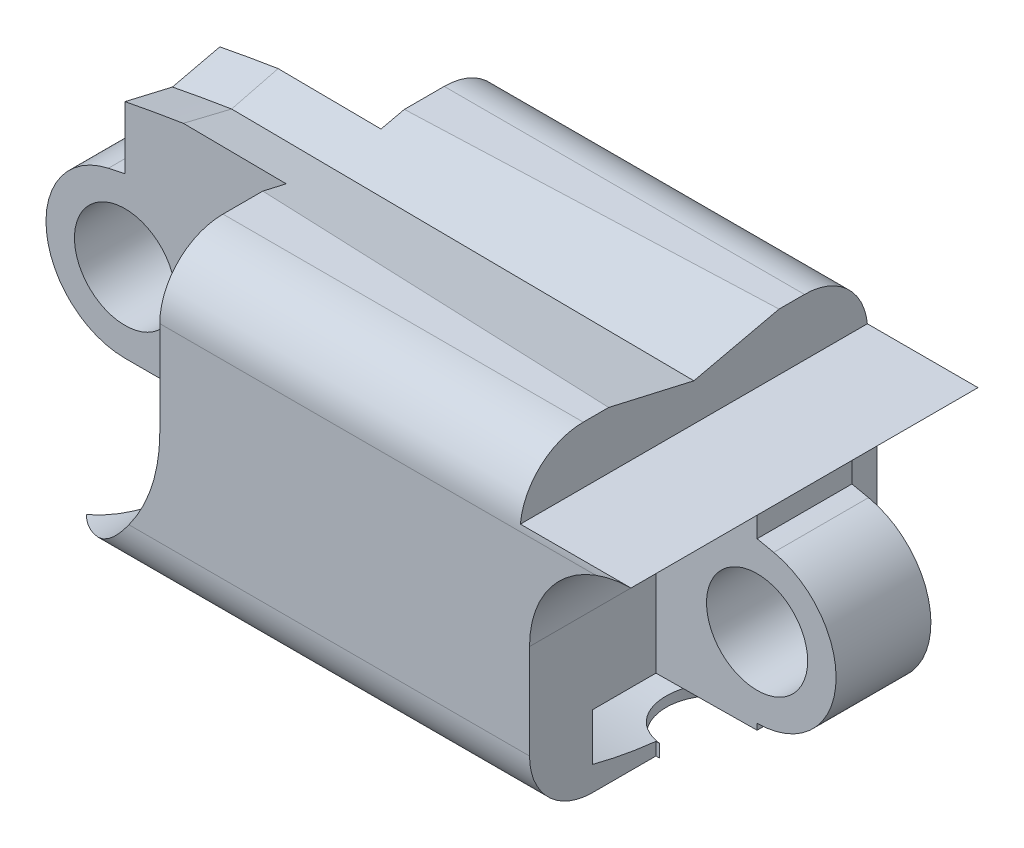
SolidWorks part; units mm, degrees
ref_plane "Front Plane" through (0, 0, 0) normal (0, 0, 1) x (1, 0, 0)
ref_plane "Top Plane" through (0, 0, 0) normal (0, 1, 0) x (1, 0, 0)
ref_plane "Right Plane" through (0, 0, 0) normal (1, 0, 0) x (0, 0, -1)
sketch "Sketch1" plane through (0, 0, 0) normal (0, 0, 1) x (1, 0, 0)
  line L0 (0, 0) -> (20, 0) construction
  line L1 (0, -2.5) -> (20, -2.5)
  circle A0 centre (0, 0) radius 1.6
  circle A1 centre (20, 0) radius 1.6
  arc A2 (-0.5263, 2.444) -> (0, -2.5) centre (0, 0) ccw
  arc A3 (20, -2.5) -> (20.5263, 2.444) centre (20, 0) ccw
  arc A4 (20.5263, 2.444) -> (-0.5263, 2.444) centre (10, -46.4354) ccw
  dimension "D2" = 3.2
  dimension "D3" = 3.2
  dimension "D4" = 5
  dimension "D5" = 5
  dimension "D6" = 50
  dimension "D1" = 20
extrude "Boss-Extrude1" add sketch "Sketch1" along normal mid plane 3
sketch "Sketch2" plane through (0, 0, 0) normal (0, 1, 0) x (1, 0, 0)
  line L0 (0, 0) -> (20, 0) construction
  line L1 (21.6, 1.5) -> (18.4, 1.5) construction
  line L2 (21.6, 1.5) -> (18.4, 1.5) construction
  line L3 (20, 1.5) -> (20, 0) construction
  line L4 (2, 0) -> (2, -5)
  line L5 (2, -5) -> (20, -5)
  line L6 (20, -5) -> (20, 0)
  line L7 (2, 0) -> (20, 0)
  dimension "D1" = 2
  dimension "D3" = 5
revolve "Revolve1" add sketch "Sketch2" angle 360 about L7
sketch "Sketch3" plane through (0, 0, 0) normal (1, 0, 0) x (0, 0, -1)
  line L0 (3.5, 5) -> (0, 4.1827)
  line L1 (0, 4.1827) -> (-3.5, 5)
  line L2 (0, 4.1827) -> (0, 0) construction
  line L3 (3.5, 5) -> (3.6816, 6.0352)
  line L5 (3.6816, 6.0352) -> (-3.5, 6.0352)
  line L7 (-3.5, 6.0352) -> (-3.5, 5)
  line L9 (-3.5, 5) -> (3.5, 5) construction
  dimension "D1" = 7
  dimension "D2" = 5
sketch "Sketch4" plane through (0, 0, 0) normal (0, 0, 1) x (1, 0, 0)
  line L0 (2, 2.9204) -> (24.8633, 2.711)
  line L1 (-0.5263, 2.444) -> (-4.0678, 1.9237)
  arc A0 (2, 2.9204) -> (-0.5263, 2.444) centre (10, -46.4354) ccw construction
  arc A1 (2, 2.9204) -> (-0.5263, 2.444) centre (10, -46.4354) ccw
sketch "Sketch9" plane through (0, 0, 0) normal (1, 0, 0) x (0, 0, -1)
  line L1 (-3.5, -5) -> (3.5, -5)
  line L2 (-5.5, -3) -> (-5.5, 3)
  line L3 (-3.5, 5) -> (3.5, 5)
  line L4 (5.5, -3) -> (5.5, 3)
  line L5 (0, 5) -> (0, -5) construction
  line L6 (-5.5, 0) -> (5.5, 0) construction
  arc A0 (3.5, 5) -> (5.5, 3) centre (3.5, 3) cw
  arc A1 (3.5, -5) -> (5.5, -3) centre (3.5, -3) ccw
  arc A2 (-3.5, -5) -> (-5.5, -3) centre (-3.5, -3) cw
  arc A3 (-5.5, 3) -> (-3.5, 5) centre (-3.5, 3) cw
  point P0 (0, 0)
  point P6 (5.5, 5)
  point P9 (5.5, -5)
  dimension "D3" = 2
  dimension "D1" = 10
  dimension "D2" = 11
extrude "Boss-Extrude3" add sketch "Sketch9" along normal blind 20
sweep "Cut-Sweep1" cut profiles "Sketch3" path "Sketch4"
sketch "Sketch6" plane through (20, 0, 0) normal (1, 0, 0) x (0, 0, -1)
  line L0 (0, 0) -> (0, -2.6933) construction
  line L1 (3.5, -2.6933) -> (3.5, -4.1933)
  line L2 (3.5, -2.6933) -> (-3.5, -2.6933)
  line L3 (-3.5, -2.6933) -> (-3.5, -4.1933)
  line L4 (-4.3454, -5.6435) -> (4.5279, -5.6435) construction
  line L5 (6.0522, -4.6435) -> (-5.5327, -4.6435) construction
  arc A3 (-3.5, -4.1933) -> (3.5, -4.1933) centre (0, 9.1842) ccw
  dimension "D1" = 1
  dimension "D2" = 1.5
  dimension "D3" = 7
sketch "Sketch7" plane through (0, 0, 0) normal (0, 0, 1) x (1, 0, 0)
  line L0 (0, -2.9117) -> (20, -2.6933)
  line L1 (0, 0) -> (0, -2.9117) construction
sweep "Cut-Sweep3" cut profiles "Sketch6" path "Sketch7"
sketch "Sketch8" plane through (0, 0, 1.5) normal (0, 0, 1) x (1, 0, 0)
  line L0 (16.8, 0) -> (16.8, -2)
  line L2 (16.8, -2) -> (16.8, -5)
  line L4 (16.8, -5) -> (20, -5)
  line L5 (20, -5) -> (20, -3.2)
  arc A1 (20, -3.2) -> (16.8, 0) centre (20, 0) ccw
  dimension "D1" = 3.2
extrude "Cut-Extrude3" cut sketch "Sketch8" along normal blind 4
sketch "Sketch5" plane through (0, 0, 1.5) normal (0, 0, 1) x (1, 0, 0)
  line L0 (5.1, 0) -> (5.1, 5.1)
  line L1 (5.1, 5.1) -> (0, 5.1)
  arc A0 (0, 5.1) -> (5.1, 0) centre (0, 0) ccw
  dimension "D1" = 10.2
extrude "Cut-Extrude1" cut sketch "Sketch5" along normal blind 4
mirror "Mirror1" about plane through (0, 0, 0) normal (0, 0, 1) of "Cut-Extrude1", "Cut-Extrude3"
sketch "Sketch10" plane through (0.0318, -2.9114, 0) normal (0.0109, -0.9999, 0) x (0.9999, 0.0109, 0)
  line L0 (17.1743, 1.5173) -> (23.5925, 1.5173)
  line L1 (23.5925, 1.5173) -> (23.5925, -1.5173)
  line L2 (23.5925, -1.5173) -> (17.1744, -1.5173)
  line L4 (17.1744, -1.5173) -> (17.0885, -1.5173)
  line L5 (17.1743, 1.5173) -> (17.0885, 1.5173)
  arc A0 (17.0885, 1.5173) -> (17.0885, -1.5173) centre (17.0885, 0) ccw
extrude "Cut-Extrude4" cut sketch "Sketch10" along normal blind 6
sketch "Sketch11" plane through (0, 0, 1.5) normal (0, 0, 1) x (1, 0, 0)
  line L0 (20, 1.6) -> (20, -1.6) construction
  line L1 (0, -1.6) -> (0, 1.6) construction
  circle A0 centre (20, 0) radius 1.6
  arc A1 (20, -1.6) -> (20, 1.6) centre (20, 0) ccw construction
  circle A2 centre (0, 0) radius 1.6
extrude "Cut-Extrude5" cut sketch "Sketch11" against normal through all both and the other way through all
sketch "Sketch12" plane through (0, 0, 1.5) normal (0, 0, 1) x (1, 0, 0)
  line L0 (2, -2.5) -> (4.4452, -2.5)
  line L1 (2, -2.5) -> (-0.9799, -2.5)
  line L2 (-0.9799, -2.5) -> (-0.9799, -5.0962)
  line L3 (-0.9799, -5.0962) -> (0.1971, -5.0962)
  arc A1 (0.1971, -5.0962) -> (4.4452, -2.5) centre (0, 0) ccw
  circle A2 centre (0, 0) radius 2.5 construction
extrude "Cut-Extrude6" cut sketch "Sketch12" against normal blind 10
sketch "Sketch13" plane through (0, -5, 0) normal (0, -1, 0) x (1, 0, 0)
  line L0 (0, 1.5) -> (0, -1.5) construction
  circle A0 centre (0, 0) radius 4.1274
extrude "Cut-Extrude7" cut sketch "Sketch13" against normal up to surface (2.5 mm away) up to face at (2.2226, -2.5, 0)
sketch "Sketch14" plane through (0, 5, 0) normal (0, 1, 0) x (1, 0, 0)
  line L0 (20, 3.5) -> (5.1, 3.5) construction
  line L1 (19.0902, 3.5) -> (15.9893, 3.5)
  line L2 (19.0902, 3.5) -> (19.0902, -3.5)
  line L3 (19.0902, -3.5) -> (15.9893, -3.5)
  line L4 (15.9893, 3.5) -> (15.9893, -3.5)
  line L5 (20, -3.5) -> (5.1, -3.5) construction
sketch "Sketch15" plane through (20, 0, 0) normal (1, 0, 0) x (0, 0, -1)
  line L0 (-2.8362, 5) -> (2.8362, 5)
  line L1 (-1.5, 3.2) -> (1.5, 3.2)
  line L9 (1.5, 3.2) -> (5.49, 3.2)
  line L10 (3.5, 5) -> (2.8362, 5)
  line L11 (2.8362, 5) -> (0, 4.3511)
  line L12 (0, 4.3511) -> (-2.8362, 5)
  line L13 (-2.8362, 5) -> (-3.5, 5)
  line L14 (-5.49, 3.2) -> (-1.5, 3.2)
  line L15 (-1.5, 3.2) -> (-1.5, 2.5544)
  line L16 (-1.5, 2.5544) -> (1.5, 2.5544)
  line L17 (1.5, 2.5544) -> (1.5, 3.2)
  line L18 (1.5, 3.2) -> (5.49, 3.2)
  line L19 (3.5, 5) -> (2.8362, 5)
  line L22 (-2.8362, 5) -> (-3.5, 5)
  line L23 (-5.49, 3.2) -> (-1.5, 3.2)
  arc A2 (5.49, 3.2) -> (3.5, 5) centre (3.5, 3) ccw
  arc A3 (-3.5, 5) -> (-5.49, 3.2) centre (-3.5, 3) ccw
  arc A4 (5.49, 3.2) -> (3.5, 5) centre (3.5, 3) ccw
  arc A5 (-3.5, 5) -> (-5.49, 3.2) centre (-3.5, 3) ccw
  dimension "D1" = 0
extrude "Cut-Extrude8" cut sketch "Sketch15" against normal blind 3.5
